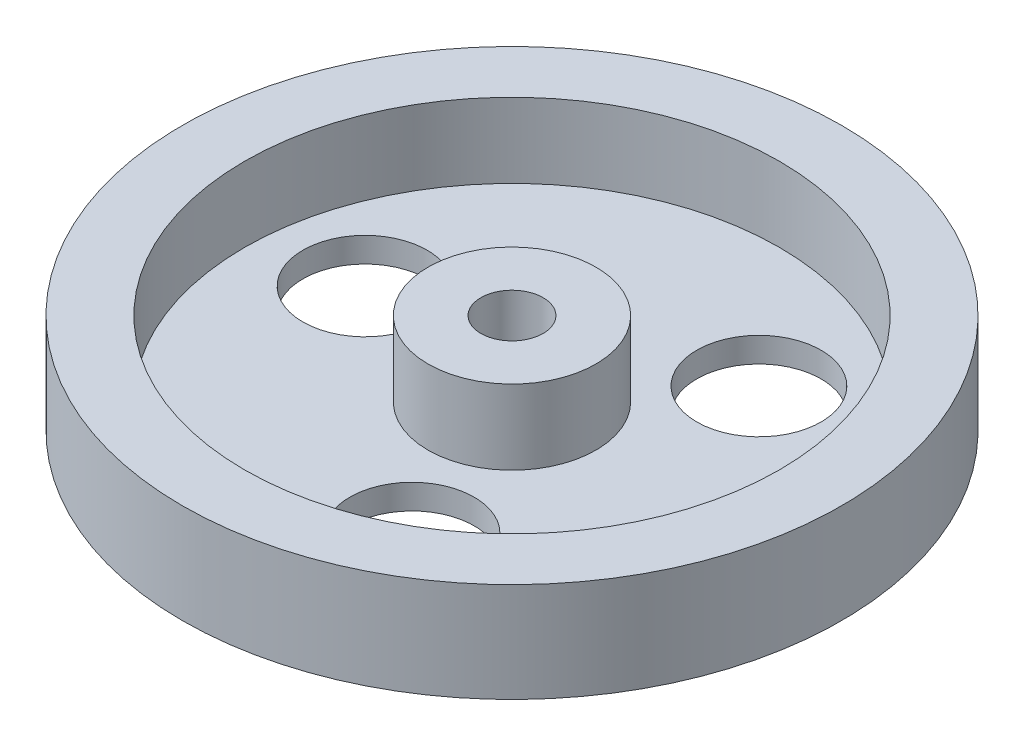
SolidWorks part; units mm, degrees
ref_plane "Plan de face" through (0, 0, 0) normal (0, 0, 1) x (1, 0, 0)
ref_plane "Plan de dessus" through (0, 0, 0) normal (0, 1, 0) x (1, 0, 0)
ref_plane "Plan de droite" through (0, 0, 0) normal (1, 0, 0) x (0, 0, -1)
sketch "Esquisse1" plane through (0, 0, 0) normal (0, 1, 0) x (1, 0, 0)
  circle A0 centre (0, 0) radius 26.5
extrude "Boss.-Extru.1" add sketch "Esquisse1" along normal blind 8
sketch "Esquisse2" plane through (0, 8, 0) normal (0, 1, 0) x (1, 0, 0)
  circle A0 centre (0, 0) radius 21.5
  circle A1 centre (0, 0) radius 6.75
  dimension "D1" = 43
  dimension "D2" = 13.5
extrude "Enlèv. mat.-Extru.1" cut sketch "Esquisse2" against normal blind 6
sketch "Esquisse3" plane through (0, 8, 0) normal (0, 1, 0) x (1, 0, 0)
  circle A0 centre (0, 0) radius 2.5
extrude "Enlèv. mat.-Extru.2" cut sketch "Esquisse3" against normal through all
sketch "Esquisse4" plane through (0, 2, 0) normal (0, 1, 0) x (-1, 0, 0)
  line L0 (10.2461, -26.3264) -> (-27.9224, 4.2899) construction
  line L1 (10.2461, -26.3264) -> (17.6763, 22.0366) construction
  line L2 (17.6763, 22.0366) -> (-27.9224, 4.2899) construction
  line L3 (-6.75, 0) -> (-21.5, 0) construction
  circle A0 centre (0, 0) radius 14.125 construction
  circle A1 centre (0, 0) radius 6.75 construction
  circle A2 centre (0, 0) radius 6.75 construction
  circle A3 centre (0, 0) radius 21.5 construction
  circle A4 centre (13.9612, -2.1449) radius 5
  circle A5 centre (-5.123, 13.1632) radius 5
  circle A6 centre (-8.8382, -11.0183) radius 5
  point P15 (-14.125, 0)
  dimension "D3" = 10
  dimension "D4" = 10
  dimension "D5" = 10
  dimension "D1" = 60
  dimension "D2" = 60
extrude "Enlèv. mat.-Extru.3" cut sketch "Esquisse4" against normal through all
